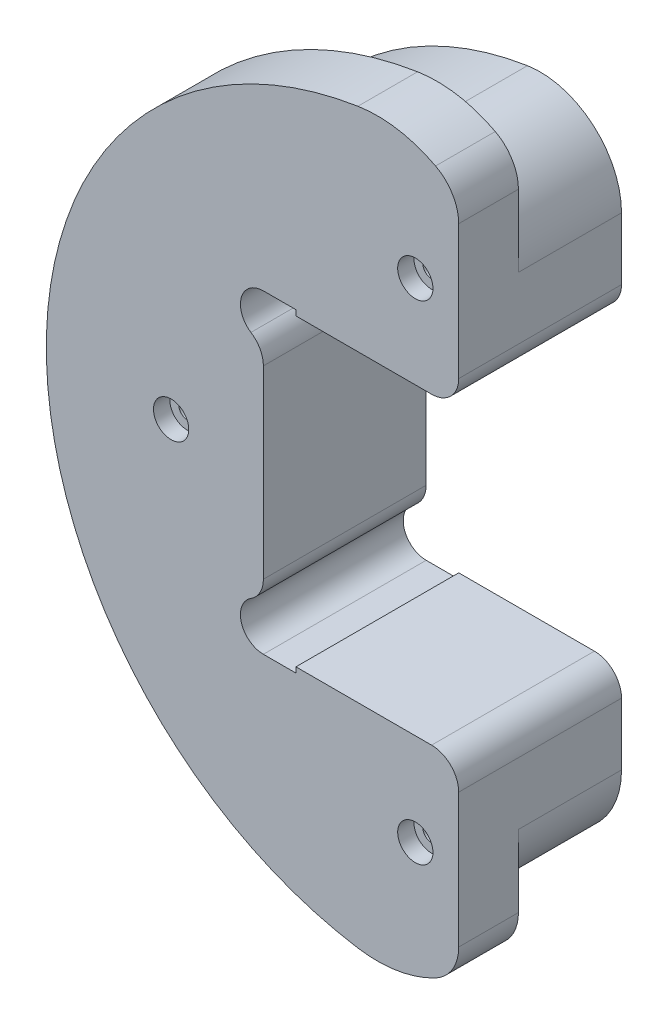
SolidWorks part; units mm, degrees
other "詳細ｱｲﾃﾑ1"
material "ABS"
ref_plane "正面" through (0, 0, 0) normal (0, 0, 1) x (1, 0, 0)
ref_plane "平面" through (0, 0, 0) normal (0, 1, 0) x (1, 0, 0)
ref_plane "右側面" through (0, 0, 0) normal (1, 0, 0) x (0, 0, -1)
sketch "ｽｹｯﾁ1" plane through (0, 0, 0) normal (0, 0, 1) x (1, 0, 0)
  line L0 (8, 59.4643) -> (8, 28)
  line L1 (0, 0) -> (-18.0429, 0) construction
  line L2 (8, 28) -> (-22, 28)
  line L3 (-22, 28) -> (-22, 29)
  line L4 (-22, 29) -> (-28, 29)
  line L5 (-28, 29) -> (-28, -29)
  line L6 (-28, -29) -> (-22, -29)
  line L7 (-22, -29) -> (-22, -28)
  line L8 (-22, -28) -> (8, -28)
  line L9 (8, -28) -> (8, -59.4643)
  line L10 (0, 0) -> (0, 45) construction
  arc A0 (8, 59.4643) -> (8, -59.4643) centre (0, 0) ccw
  point P6 (0, 45)
  point P19 (45, 0)
  point P20 (0, -45)
  point P21 (-45, 0)
  point P22 (0, 0)
  dimension "D1" = 8
  dimension "D2" = 120
  dimension "D3" = 1
  dimension "D4" = 6
  dimension "D5" = 22
  dimension "D6" = 58
  dimension "D7" = 45
  dimension "D8" = 4
extrude "ﾎﾞｽ - 押し出し1" add sketch "ｽｹｯﾁ1" along normal blind 30
hole_wizard "M3 穴付きねじ用座ぐり穴1" positions "3Dｽｹｯﾁ1" profile "ｽｹｯﾁ2" counterbore size "M3" standard "JIS" end condition through all
sketch3d "3Dｽｹｯﾁ1"
  point P0 (0, 45, 30)
  point P2 (-45, 0, 30)
  point P4 (0, -45, 30)
sketch "ｽｹｯﾁ2" plane through (0, 45, 30) normal (1, 0, 0) x (0, -1, 0)
  line L0 (0, 0) -> (0, 30)
  line L1 (0, 30) -> (1.6, 30)
  line L3 (1.6, 30) -> (1.6, 3)
  line L4 (1.6, 3) -> (3.25, 3)
  line L5 (3.25, 3) -> (3.25, 0)
  line L7 (3.25, 0) -> (0, 0)
  line L11 (0, -6.35) -> (0, 107.95) construction
  dimension "通し穴の直径" = 3.2
  dimension "通し穴の深さ" = 30
  dimension "座ぐり穴の直径" = 6.5
  dimension "座ぐり穴の深さ" = 3
fillet "ﾌｨﾚｯﾄ1" radius 15 2 edges at (8, -59.4643, 15) (8, 59.4643, 15)
sketch "ｽｹｯﾁ3" plane through (0, 0, 0) normal (0, 0, 1) x (1, 0, 0)
  line L0 (-28, -29) -> (-28, 29) construction
  line L2 (-28, 27.75) -> (-31, 27.75) construction
  line L3 (-28, 27.75) -> (-28, 22.25) construction
  line L4 (-28, 22.25) -> (-31, 22.25) construction
  line L5 (-31, 27.75) -> (-31, 22.25) construction
  line L6 (-28, 29) -> (-22, 29) construction
  line L7 (-28, 29) -> (-28, 20.55)
  line L8 (0, 0) -> (50000, 0) construction
  line L9 (-28, -29) -> (-28, -20.55)
  arc A0 (-28, 29) -> (-28, 20.55) centre (-28, 24.775) ccw
  arc A1 (-28, -29) -> (-28, -20.55) centre (-28, -24.775) cw
  dimension "D1" = 1.25
  dimension "D2" = 5.5
  dimension "D3" = 3
extrude "ねじ頭よけ" cut sketch "ｽｹｯﾁ3" along normal through all
fillet "ﾌｨﾚｯﾄ2" radius 5 4 edges at (8, 28, 15) (8, -28, 15) (-28, -20.55, 15) (-28, 20.55, 15)
sketch "ｽｹｯﾁ4" plane through (0, 0, 30) normal (0, 0, 1) x (1, 0, 0)
  line L0 (8, 44.4522) -> (8, 61.8878)
  line L2 (8, -44.4522) -> (8, -61.8878)
  arc A0 (-9.3333, -59.2696) -> (8, -44.4522) centre (-7, -44.4522) ccw construction
  arc A1 (8, 44.4522) -> (-9.3333, 59.2696) centre (-7, 44.4522) ccw construction
  arc A2 (-9.3333, 59.2696) -> (-9.3333, -59.2696) centre (0, 0) ccw construction
  arc A3 (-9.3333, -59.2696) -> (8, -44.4522) centre (-7, -44.4522) ccw
  arc A4 (8, 44.4522) -> (-9.3333, 59.2696) centre (-7, 44.4522) ccw
  arc A5 (-9.3333, 59.2696) -> (-9.3333, -59.2696) centre (0, 0) ccw
  arc A10 (-10.5778, -67.1722) -> (16, -44.4522) centre (-7, -44.4522) ccw
  arc A11 (16, 44.4522) -> (-10.5778, 67.1722) centre (-7, 44.4522) ccw
  arc A12 (-10.5778, 67.1722) -> (-10.5778, -67.1722) centre (0, 0) ccw
  arc A13 (-10.5778, -67.1722) -> (8, -61.8878) centre (-7, -44.4522) ccw
  arc A14 (8, 61.8878) -> (-10.5778, 67.1722) centre (-7, 44.4522) ccw
  arc A15 (-10.5778, 67.1722) -> (-10.5778, -67.1722) centre (0, 0) ccw
  dimension "D1" = 8
extrude "ﾎﾞｽ - 押し出し2" add sketch "ｽｹｯﾁ4" against normal blind 11
fillet "ﾌｨﾚｯﾄ3" radius 8 2 edges at (8, 61.8878, 24.5) (8, -61.8878, 24.5)
ref_plane "底面" through (0, 0, 31) normal (0, 0, 1) x (1, 0, 0)
equation "\"ミル径\"= 1"
equation "\"コーナR面取り小\"= 2"
equation "\"コーナR面取り大\"= 5"
equation "\"D1@ﾌｨﾚｯﾄ2\"=\"コーナR面取り大\""
